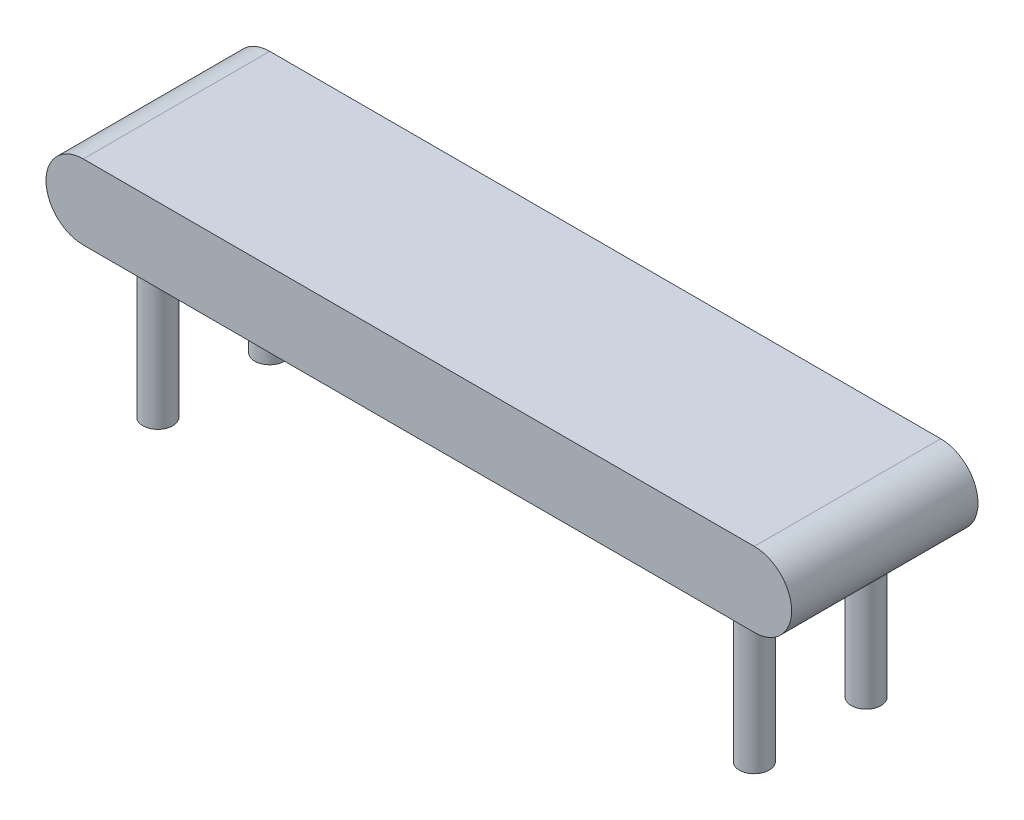
SolidWorks part; units mm, degrees
ref_plane "Front Plane" through (0, 0, 0) normal (0, 0, 1) x (1, 0, 0)
ref_plane "Top Plane" through (0, 0, 0) normal (0, 1, 0) x (1, 0, 0)
ref_plane "Right Plane" through (0, 0, 0) normal (1, 0, 0) x (0, 0, -1)
sketch "Sketch1" plane through (0, 0, 0) normal (0, 1, 0) x (1, 0, 0)
  line L1 (-500, -125) -> (500, -125)
  line L2 (-500, -125) -> (-500, 125)
  line L3 (-500, 125) -> (500, 125)
  line L4 (500, -125) -> (500, 125)
  line L5 (0, 125) -> (0, -125) construction
  line L6 (-500, 0) -> (500, 0) construction
  point P0 (0, 0)
  dimension "D1" = 1000
  dimension "D2" = 250
extrude "Boss-Extrude1" add sketch "Sketch1" along normal blind 100
sketch "Sketch2" plane through (0, 0, 125) normal (0, 0, 1) x (1, 0, 0)
  line L0 (-500, 100) -> (-500, 0) construction
  line L2 (0, -55) -> (0, 55) construction
  line L3 (450, 100) -> (500, 100)
  line L4 (500, 100) -> (500, 0)
  line L5 (500, 100) -> (500, 0) construction
  line L6 (500, 0) -> (450, 0)
  line L7 (-450, 100) -> (-500, 100)
  line L8 (-500, 100) -> (-500, 0)
  line L9 (-500, 0) -> (-450, 0)
  arc A0 (-450, 100) -> (-450, 0) centre (-450, 50) ccw
  arc A1 (450, 100) -> (450, 0) centre (450, 50) cw
  line M2 (-500, 0) -> (500, 0)
  line M3 (500, 0) -> (500, 100)
  line M4 (500, 100) -> (-500, 100)
  line M5 (-500, 100) -> (-500, 0)
  dimension "D1" = 100
  dimension "D2" = 50
extrude "Cut-Extrude1" cut sketch "Sketch2" against normal through all contours A0 M4 M5 | A0 L8 M2 | A1 L4 M4 | A1 M3 M2
sketch "Sketch3" plane through (0, 0, 0) normal (0, -1, 0) x (1, 0, 0)
  line L0 (-450, 125) -> (450, 125) construction
  line L1 (-450, -125) -> (-450, 125) construction
  line L2 (0, -55) -> (0, 55) construction
  line L4 (55, 0) -> (-55, 0) construction
  circle A0 centre (-400, 75) radius 20
  circle A1 centre (400, 75) radius 20
  circle A2 centre (400, -75) radius 20
  circle A3 centre (-400, -75) radius 20
  dimension "D3" = 40
  dimension "D1" = 50
  dimension "D2" = 50
extrude "Boss-Extrude2" add sketch "Sketch3" along normal blind 200
